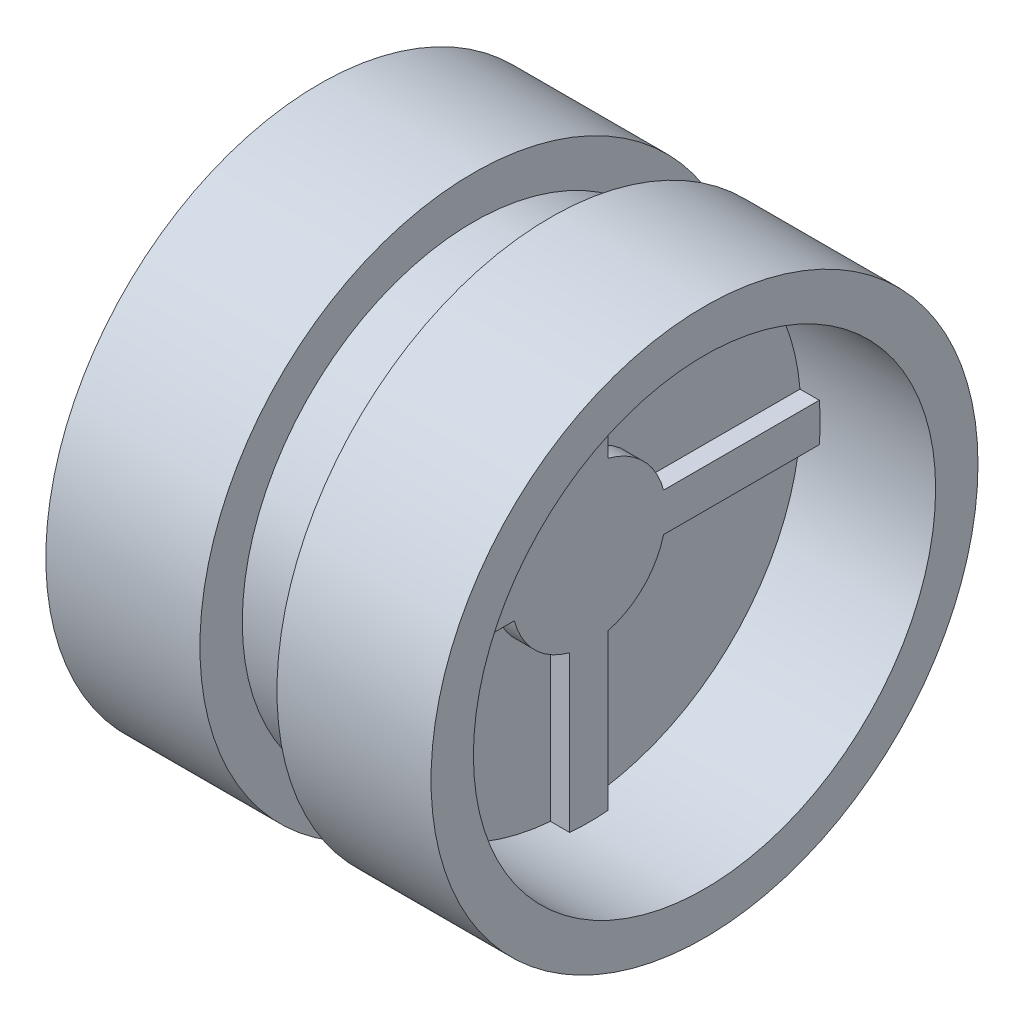
SolidWorks part; units mm, degrees
ref_plane "Front Plane" through (0, 0, 0) normal (0, 0, 1) x (1, 0, 0)
ref_plane "Top Plane" through (0, 0, 0) normal (0, 1, 0) x (1, 0, 0)
ref_plane "Right Plane" through (0, 0, 0) normal (1, 0, 0) x (0, 0, -1)
sketch "Sketch1" plane through (0, 0, 0) normal (0, 0, 1) x (1, 0, 0)
  line L0 (0, 0) -> (-5, 0)
  line L1 (-5, 0) -> (-5, 3)
  line L2 (-5, 3) -> (-1.5, 3)
  line L3 (-1.5, 3) -> (-1.5, 6)
  line L4 (-1.5, 6) -> (-5, 6)
  line L5 (-5, 6) -> (-5, 7.1)
  line L6 (-5, 7.1) -> (-1, 7.1)
  line L7 (-1, 7.1) -> (-1, 6)
  line L8 (-1, 6) -> (1, 6)
  line L9 (0, 6) -> (0, 0) construction
  line L10 (5, 6) -> (5, 7.1)
  line L11 (1.5, 6) -> (5, 6)
  line L12 (1, 7.1) -> (1, 6)
  line L13 (5, 7.1) -> (1, 7.1)
  line L14 (1.5, 6) -> (1.5, 0)
  line L15 (1.5, 0) -> (0, 0)
  dimension "D1" = 5
  dimension "D2" = 3
  dimension "D3" = 3
  dimension "D4" = 3.5
  dimension "D5" = 3.5
  dimension "D6" = 4
revolve "Revolve1" add sketch "Sketch1" angle 360 about L15
sketch "Sketch2" plane through (0, 0, 0) normal (1, 0, 0) x (0, 0, -1)
  line L1 (0.5, 1.9365) -> (0.5, 5.9791)
  line L2 (-0.5, 1.9365) -> (-0.5, 5.9791)
  line L3 (1.9365, -0.5) -> (5.9791, -0.5)
  line L6 (1.9365, 0.5) -> (5.9791, 0.5)
  line L7 (-0.5, -1.9365) -> (-0.5, -5.9791)
  line L8 (0.5, -1.9365) -> (0.5, -5.9791)
  line L9 (-1.9365, 0.5) -> (-5.9791, 0.5)
  line L10 (-1.9365, -0.5) -> (-5.9791, -0.5)
  arc A0 (1.9365, 0.5) -> (0.5, 1.9365) centre (0, 0) ccw
  arc A1 (-0.5, 1.9365) -> (-1.9365, 0.5) centre (0, 0) ccw
  arc A2 (0.5, 5.9791) -> (-0.5, 5.9791) centre (0, 0) ccw
  arc A3 (-1.9365, -0.5) -> (-0.5, -1.9365) centre (0, 0) ccw
  arc A4 (0.5, -1.9365) -> (1.9365, -0.5) centre (0, 0) ccw
  arc A5 (-5.9791, 0.5) -> (-5.9791, -0.5) centre (0, 0) ccw
  arc A6 (5.9791, -0.5) -> (5.9791, 0.5) centre (0, 0) ccw
  arc A7 (-0.5, -5.9791) -> (0.5, -5.9791) centre (0, 0) ccw
  point P2 (0.5, 0)
  point P4 (0, 6)
  point P5 (0.5, 6)
  point P6 (-0.5, 0)
  point P7 (-0.5, 6)
  point P28 (0, 0)
  dimension "D1" = 4
  dimension "D4" = 4
extrude "Boss-Extrude2" add sketch "Sketch2" along normal blind 2 contours L8 A4 L3 A2 L6 A0 L1 L2 A1 L9 L10 A3 L7
sketch "Sketch3" plane through (-5, 0, 0) normal (-1, 0, 0) x (0, 0, 1)
  circle A0 centre (0, 0) radius 1.5
  dimension "D1" = 3
extrude "Cut-Extrude2" cut sketch "Sketch3" against normal blind 5 contours A0
